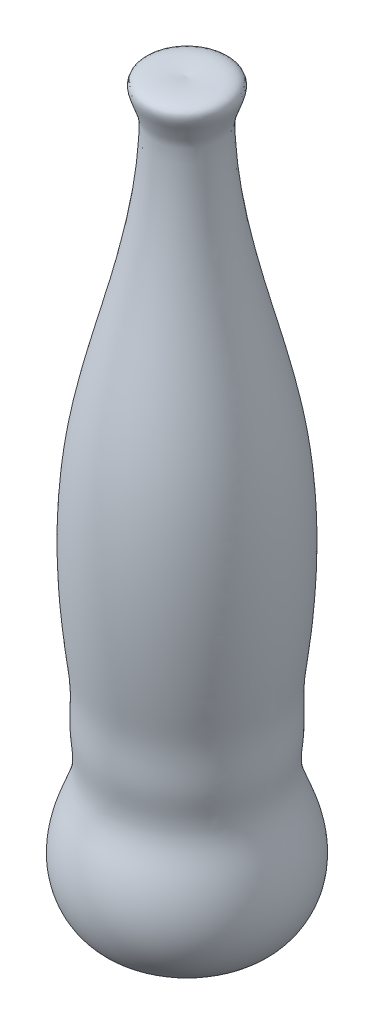
SolidWorks part; units mm, degrees
ref_plane "Alzado" through (0, 0, 0) normal (0, 0, 1) x (1, 0, 0)
ref_plane "Planta" through (0, 0, 0) normal (0, 1, 0) x (1, 0, 0)
ref_plane "Vista lateral" through (0, 0, 0) normal (1, 0, 0) x (0, 0, -1)
sketch "Croquis1" plane through (0, 0, 0) normal (0, 0, 1) x (1, 0, 0)
  line L0 (188.7226, 631.7431) -> (828.7226, 631.7431) construction
  line L1 (0, 29.8475) -> (0, -17.0019) construction
  line L2 (0, -13.937) -> (0, 28.5817)
  spline S0 degree 3 poles (0, -13.937) (1.3555, -13.9829) (4.2191, -14.0767) (5.9883, -10.7038) (5.5036, -8.0501) (4.4433, -5.8536) (4.8384, -3.8017) (4.6606, -1.8731) (5.0694, 1.0371) (5.3973, 5.3254) (5.0007, 11.7442) (3.3041, 17.2765) (2.2481, 22.2853) (1.9617, 24.7918) (1.9096, 27.6035) (3.8084, 29.0891) (0, 28.5817) knots 0 0 0 0 0.090813 0.144815 0.209981 0.251517 0.291138 0.334316 0.370755 0.471483 0.599535 0.764051 0.826503 0.915117 0.918715 1 1 1 1
  point P7 (0, 0)
  point P9 (2.078, 27.6706)
  point P11 (0, 0)
  point P13 (0, 0)
  point P15 (2.4508, 27.2357)
  point P17 (0, 28.5817)
  point P19 (0, 0)
  point P21 (0, 0)
  point P23 (2.8649, 27.4635)
  point P25 (2.3472, 27.7534)
revolve "Revolución2" add sketch "Croquis1" angle 360 about L2
